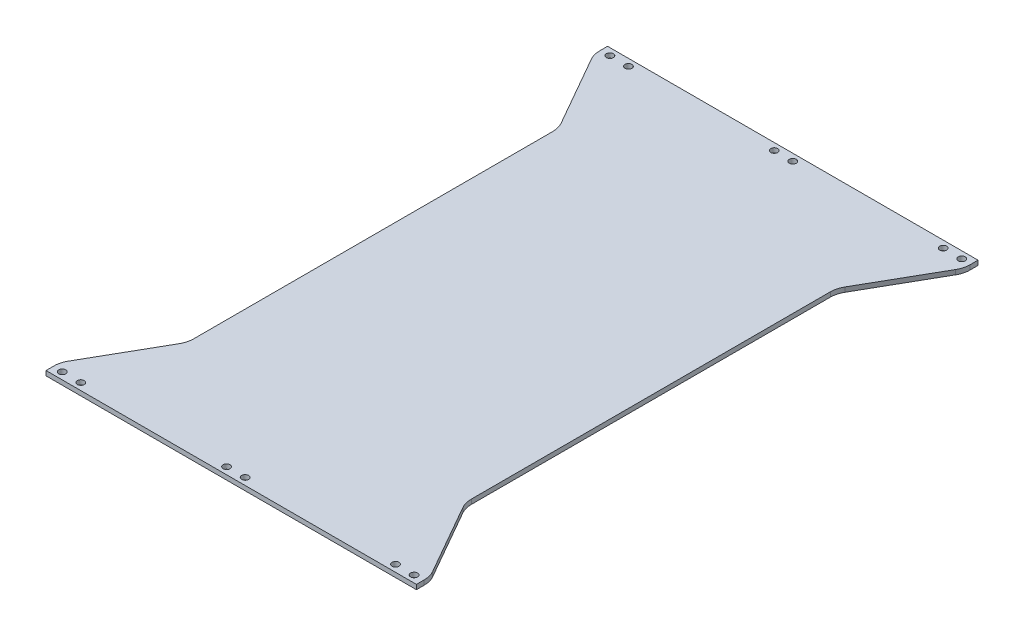
SolidWorks part; units mm, degrees
ref_plane "Front Plane" through (0, 0, 0) normal (0, 0, 1) x (1, 0, 0)
ref_plane "Top Plane" through (0, 0, 0) normal (0, 1, 0) x (1, 0, 0)
ref_plane "Right Plane" through (0, 0, 0) normal (1, 0, 0) x (0, 0, -1)
sketch "Sketch1" plane through (0, 0, 0) normal (0, 1, 0) x (1, 0, 0)
  line L0 (845.6879, -1714.9186) -> (845.6879, -1716.9186) construction
  line L1 (843.6879, -1712.9186) -> (831.6879, -1712.9186) construction
  line L2 (829.6879, -1714.9186) -> (829.6879, -1716.9186) construction
  line L3 (774.8679, -1714.9186) -> (774.8679, -1716.9186) construction
  line L4 (758.8679, -1714.9186) -> (758.8679, -1716.9186) construction
  line L5 (760.8679, -1712.9186) -> (772.8679, -1712.9186) construction
  line L6 (702.0529, -1714.9186) -> (702.0529, -1716.9186) construction
  line L7 (700.0529, -1712.9186) -> (688.0529, -1712.9186) construction
  line L8 (686.0529, -1714.9186) -> (686.0529, -1716.9186) construction
  line L9 (847.6829, -1480.9186) -> (847.6829, -1478.9186) construction
  line L10 (833.6829, -1482.9186) -> (845.6829, -1482.9186) construction
  line L11 (831.6829, -1480.9186) -> (831.6829, -1478.9186) construction
  line L12 (774.8679, -1480.9186) -> (774.8679, -1478.9186) construction
  line L13 (772.8679, -1482.9186) -> (760.8679, -1482.9186) construction
  line L14 (758.8679, -1480.9186) -> (758.8679, -1478.9186) construction
  line L15 (704.0479, -1480.9186) -> (704.0479, -1478.9186) construction
  line L16 (690.0479, -1482.9186) -> (702.0479, -1482.9186) construction
  line L17 (688.0479, -1480.9186) -> (688.0479, -1478.9186) construction
  line L18 (845.6879, -1714.9186) -> (845.6879, -1716.9186) construction
  line L19 (843.6879, -1712.9186) -> (831.6879, -1712.9186) construction
  line L20 (829.6879, -1714.9186) -> (829.6879, -1716.9186) construction
  line L21 (774.8679, -1714.9186) -> (774.8679, -1716.9186) construction
  line L22 (758.8679, -1714.9186) -> (758.8679, -1716.9186) construction
  line L23 (760.8679, -1712.9186) -> (772.8679, -1712.9186) construction
  line L24 (702.0529, -1714.9186) -> (702.0529, -1716.9186) construction
  line L25 (700.0529, -1712.9186) -> (688.0529, -1712.9186) construction
  line L26 (686.0529, -1714.9186) -> (686.0529, -1716.9186) construction
  line L27 (847.6829, -1480.9186) -> (847.6829, -1478.9186) construction
  line L28 (833.6829, -1482.9186) -> (845.6829, -1482.9186) construction
  line L29 (831.6829, -1480.9186) -> (831.6829, -1478.9186) construction
  line L30 (774.8679, -1480.9186) -> (774.8679, -1478.9186) construction
  line L31 (772.8679, -1482.9186) -> (760.8679, -1482.9186) construction
  line L32 (758.8679, -1480.9186) -> (758.8679, -1478.9186) construction
  line L33 (704.0479, -1480.9186) -> (704.0479, -1478.9186) construction
  line L34 (690.0479, -1482.9186) -> (702.0479, -1482.9186) construction
  line L35 (688.0479, -1480.9186) -> (688.0479, -1478.9186) construction
  line L36 (686.0479, -1476.9186) -> (849.6829, -1476.9186) construction
  line L37 (684.0529, -1718.9186) -> (847.6879, -1718.9186) construction
  circle A0 centre (833.6879, -1715.9186) radius 1.5 construction
  circle A1 centre (841.6879, -1715.9186) radius 1.5 construction
  arc A2 (845.6879, -1716.9186) -> (847.6879, -1718.9186) centre (847.6879, -1716.9186) ccw construction
  arc A3 (845.6879, -1714.9186) -> (843.6879, -1712.9186) centre (843.6879, -1714.9186) ccw construction
  arc A4 (831.6879, -1712.9186) -> (829.6879, -1714.9186) centre (831.6879, -1714.9186) ccw construction
  arc A5 (827.6879, -1718.9186) -> (829.6879, -1716.9186) centre (827.6879, -1716.9186) ccw construction
  circle A6 centre (770.8679, -1715.9186) radius 1.5 construction
  arc A7 (774.8679, -1716.9186) -> (776.8679, -1718.9186) centre (776.8679, -1716.9186) ccw construction
  arc A8 (774.8679, -1714.9186) -> (772.8679, -1712.9186) centre (772.8679, -1714.9186) ccw construction
  arc A9 (756.8679, -1718.9186) -> (758.8679, -1716.9186) centre (756.8679, -1716.9186) ccw construction
  arc A10 (760.8679, -1712.9186) -> (758.8679, -1714.9186) centre (760.8679, -1714.9186) ccw construction
  circle A11 centre (762.8679, -1715.9186) radius 1.5 construction
  circle A12 centre (690.0529, -1715.9186) radius 1.5 construction
  circle A13 centre (698.0529, -1715.9186) radius 1.5 construction
  arc A14 (702.0529, -1716.9186) -> (704.0529, -1718.9186) centre (704.0529, -1716.9186) ccw construction
  arc A15 (702.0529, -1714.9186) -> (700.0529, -1712.9186) centre (700.0529, -1714.9186) ccw construction
  arc A16 (688.0529, -1712.9186) -> (686.0529, -1714.9186) centre (688.0529, -1714.9186) ccw construction
  arc A17 (684.0529, -1718.9186) -> (686.0529, -1716.9186) centre (684.0529, -1716.9186) ccw construction
  circle A18 centre (835.6829, -1479.9186) radius 1.5 construction
  circle A19 centre (843.6829, -1479.9186) radius 1.5 construction
  arc A20 (849.6829, -1476.9186) -> (847.6829, -1478.9186) centre (849.6829, -1478.9186) ccw construction
  arc A21 (845.6829, -1482.9186) -> (847.6829, -1480.9186) centre (845.6829, -1480.9186) ccw construction
  arc A22 (831.6829, -1480.9186) -> (833.6829, -1482.9186) centre (833.6829, -1480.9186) ccw construction
  arc A23 (831.6829, -1478.9186) -> (829.6829, -1476.9186) centre (829.6829, -1478.9186) ccw construction
  circle A24 centre (762.8679, -1479.9186) radius 1.5 construction
  circle A25 centre (770.8679, -1479.9186) radius 1.5 construction
  arc A26 (776.8679, -1476.9186) -> (774.8679, -1478.9186) centre (776.8679, -1478.9186) ccw construction
  arc A27 (772.8679, -1482.9186) -> (774.8679, -1480.9186) centre (772.8679, -1480.9186) ccw construction
  arc A28 (758.8679, -1480.9186) -> (760.8679, -1482.9186) centre (760.8679, -1480.9186) ccw construction
  arc A29 (758.8679, -1478.9186) -> (756.8679, -1476.9186) centre (756.8679, -1478.9186) ccw construction
  arc A30 (706.0479, -1476.9186) -> (704.0479, -1478.9186) centre (706.0479, -1478.9186) ccw construction
  arc A31 (702.0479, -1482.9186) -> (704.0479, -1480.9186) centre (702.0479, -1480.9186) ccw construction
  circle A32 centre (700.0479, -1479.9186) radius 1.5 construction
  circle A33 centre (692.0479, -1479.9186) radius 1.5 construction
  arc A34 (688.0479, -1480.9186) -> (690.0479, -1482.9186) centre (690.0479, -1480.9186) ccw construction
  arc A35 (688.0479, -1478.9186) -> (686.0479, -1476.9186) centre (686.0479, -1478.9186) ccw construction
  circle A36 centre (833.6879, -1715.9186) radius 1.5 construction
  circle A37 centre (841.6879, -1715.9186) radius 1.5 construction
  arc A38 (845.6879, -1716.9186) -> (847.6879, -1718.9186) centre (847.6879, -1716.9186) ccw construction
  arc A39 (845.6879, -1714.9186) -> (843.6879, -1712.9186) centre (843.6879, -1714.9186) ccw construction
  arc A40 (831.6879, -1712.9186) -> (829.6879, -1714.9186) centre (831.6879, -1714.9186) ccw construction
  arc A41 (827.6879, -1718.9186) -> (829.6879, -1716.9186) centre (827.6879, -1716.9186) ccw construction
  circle A42 centre (770.8679, -1715.9186) radius 1.5 construction
  arc A43 (774.8679, -1716.9186) -> (776.8679, -1718.9186) centre (776.8679, -1716.9186) ccw construction
  arc A44 (774.8679, -1714.9186) -> (772.8679, -1712.9186) centre (772.8679, -1714.9186) ccw construction
  arc A45 (756.8679, -1718.9186) -> (758.8679, -1716.9186) centre (756.8679, -1716.9186) ccw construction
  arc A46 (760.8679, -1712.9186) -> (758.8679, -1714.9186) centre (760.8679, -1714.9186) ccw construction
  circle A47 centre (762.8679, -1715.9186) radius 1.5 construction
  circle A48 centre (690.0529, -1715.9186) radius 1.5 construction
  circle A49 centre (698.0529, -1715.9186) radius 1.5 construction
  arc A50 (702.0529, -1716.9186) -> (704.0529, -1718.9186) centre (704.0529, -1716.9186) ccw construction
  arc A51 (702.0529, -1714.9186) -> (700.0529, -1712.9186) centre (700.0529, -1714.9186) ccw construction
  arc A52 (688.0529, -1712.9186) -> (686.0529, -1714.9186) centre (688.0529, -1714.9186) ccw construction
  arc A53 (684.0529, -1718.9186) -> (686.0529, -1716.9186) centre (684.0529, -1716.9186) ccw construction
  circle A54 centre (835.6829, -1479.9186) radius 1.5 construction
  circle A55 centre (843.6829, -1479.9186) radius 1.5 construction
  arc A56 (849.6829, -1476.9186) -> (847.6829, -1478.9186) centre (849.6829, -1478.9186) ccw construction
  arc A57 (845.6829, -1482.9186) -> (847.6829, -1480.9186) centre (845.6829, -1480.9186) ccw construction
  arc A58 (831.6829, -1480.9186) -> (833.6829, -1482.9186) centre (833.6829, -1480.9186) ccw construction
  arc A59 (831.6829, -1478.9186) -> (829.6829, -1476.9186) centre (829.6829, -1478.9186) ccw construction
  circle A60 centre (762.8679, -1479.9186) radius 1.5 construction
  circle A61 centre (770.8679, -1479.9186) radius 1.5 construction
  arc A62 (776.8679, -1476.9186) -> (774.8679, -1478.9186) centre (776.8679, -1478.9186) ccw construction
  arc A63 (772.8679, -1482.9186) -> (774.8679, -1480.9186) centre (772.8679, -1480.9186) ccw construction
  arc A64 (758.8679, -1480.9186) -> (760.8679, -1482.9186) centre (760.8679, -1480.9186) ccw construction
  arc A65 (758.8679, -1478.9186) -> (756.8679, -1476.9186) centre (756.8679, -1478.9186) ccw construction
  arc A66 (706.0479, -1476.9186) -> (704.0479, -1478.9186) centre (706.0479, -1478.9186) ccw construction
  arc A67 (702.0479, -1482.9186) -> (704.0479, -1480.9186) centre (702.0479, -1480.9186) ccw construction
  circle A68 centre (700.0479, -1479.9186) radius 1.5 construction
  circle A69 centre (692.0479, -1479.9186) radius 1.5 construction
  arc A70 (688.0479, -1480.9186) -> (690.0479, -1482.9186) centre (690.0479, -1480.9186) ccw construction
  arc A71 (688.0479, -1478.9186) -> (686.0479, -1476.9186) centre (686.0479, -1478.9186) ccw construction
sketch "Sketch2" plane through (0, 0, 0) normal (0, 1, 0) x (1, 0, 0)
  line L0 (688.0479, -1476.9186) -> (688.0479, -1482.9186)
  line L1 (686.0479, -1476.9186) -> (849.6829, -1476.9186) construction
  line L2 (688.0479, -1482.9186) -> (708.0479, -1517.9186)
  line L3 (708.0479, -1517.9186) -> (708.0479, -1677.9186)
  line L4 (767.8654, -1476.9186) -> (767.8654, -1718.9186) construction
  line L5 (688.0479, -1480.9186) -> (688.0479, -1478.9186) construction
  line L6 (688.0479, -1476.9186) -> (847.6829, -1476.9186)
  line L7 (684.0529, -1718.9186) -> (847.6879, -1718.9186) construction
  line L8 (847.6829, -1476.9186) -> (847.6829, -1482.9186)
  line L9 (847.6829, -1482.9186) -> (827.6829, -1517.9186)
  line L10 (827.6829, -1517.9186) -> (827.6829, -1677.9186)
  line L11 (708.0479, -1597.9186) -> (827.6829, -1597.9186) construction
  line L12 (847.6829, -1712.9186) -> (827.6829, -1677.9186)
  line L13 (847.6829, -1718.9186) -> (847.6829, -1712.9186)
  line L14 (688.0479, -1718.9186) -> (847.6829, -1718.9186)
  line L15 (688.0479, -1712.9186) -> (708.0479, -1677.9186)
  line L16 (688.0479, -1718.9186) -> (688.0479, -1712.9186)
  circle A6 centre (843.6829, -1479.9186) radius 1.5 construction
  circle A7 centre (835.6829, -1479.9186) radius 1.5 construction
  circle A8 centre (762.8679, -1479.9186) radius 1.5 construction
  circle A9 centre (770.8679, -1479.9186) radius 1.5 construction
  circle A10 centre (700.0479, -1479.9186) radius 1.5 construction
  circle A11 centre (692.0479, -1479.9186) radius 1.5 construction
  circle A18 centre (843.6829, -1479.9186) radius 1.5
  circle A19 centre (835.6829, -1479.9186) radius 1.5
  circle A20 centre (762.8679, -1479.9186) radius 1.5
  circle A21 centre (770.8679, -1479.9186) radius 1.5
  circle A22 centre (700.0479, -1479.9186) radius 1.5
  circle A23 centre (692.0479, -1479.9186) radius 1.5
  circle A24 centre (692.0479, -1715.9186) radius 1.5
  circle A25 centre (700.0479, -1715.9186) radius 1.5
  circle A26 centre (770.8679, -1715.9186) radius 1.5
  circle A27 centre (762.8679, -1715.9186) radius 1.5
  circle A28 centre (835.6829, -1715.9186) radius 1.5
  circle A29 centre (843.6829, -1715.9186) radius 1.5
  point P46 (767.8654, -1597.9186)
  point P49 (767.8654, -1476.9186)
  dimension "D1" = 6
  dimension "D2" = 20
  dimension "D3" = 35
extrude "Boss-Extrude1" add sketch "Sketch2" along normal blind 2
fillet "Fillet1" radius 10 8 edges at (708.0479, 1, 1677.9186) (688.0479, 1, 1712.9186) (847.6829, 1, 1712.9186) (827.6829, 1, 1677.9186) (847.6829, 1, 1482.9186) (827.6829, 1, 1517.9186) (688.0479, 1, 1482.9186) (708.0479, 1, 1517.9186)
